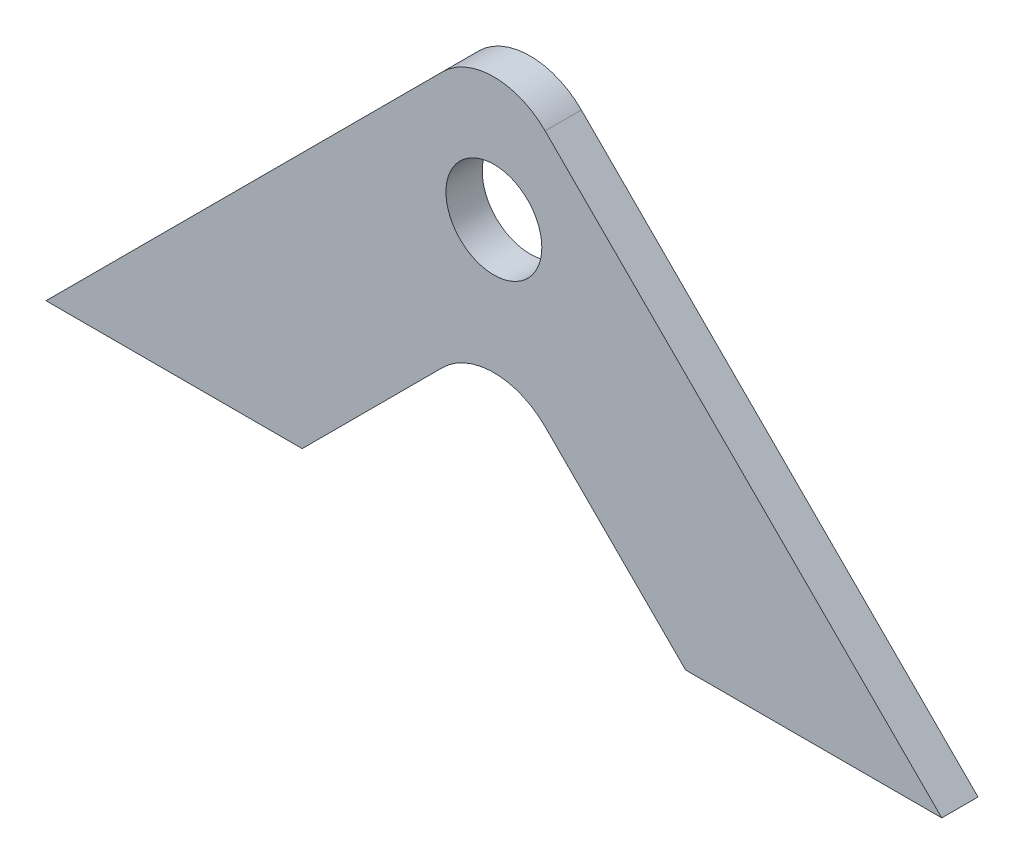
SolidWorks part; units mm, degrees
material "AISI 4130 Steel, annealed at 865C"
ref_plane "Front Plane" through (0, 0, 0) normal (0, 0, 1) x (1, 0, 0)
ref_plane "Top Plane" through (0, 0, 0) normal (0, 1, 0) x (1, 0, 0)
ref_plane "Right Plane" through (0, 0, 0) normal (1, 0, 0) x (0, 0, -1)
sketch "Sketch1" plane through (0, 0, 0) normal (0, 0, 1) x (1, 0, 0)
  line L3 (0, 0) -> (38.1, 38.0993) construction
  line L4 (0, 0) -> (76.2, 0) construction
  line L5 (38.1, 38.0993) -> (76.2, 0) construction
  line L6 (-13.4705, 0) -> (33.6099, 47.0795)
  line L7 (42.5901, 47.0795) -> (89.6705, 0)
  line L8 (89.6705, 0) -> (-13.4705, 0)
  line L9 (8.9803, 0) -> (33.6099, 24.6291)
  line L10 (42.5901, 24.6291) -> (67.2197, 0)
  line L11 (-1.1513, 12.319) -> (77.3513, 12.319)
  circle A0 centre (38.1, 38.0993) radius 4.1999
  arc A1 (33.6099, 24.6291) -> (42.5901, 24.6291) centre (38.1, 20.1389) cw
  arc A2 (42.5901, 47.0795) -> (33.6099, 47.0795) centre (38.1, 42.5894) ccw
  point P6 (38.1, 0)
  dimension "D3" = 8.3998
  dimension "D4" = 9.525
  dimension "D7" = 6.35
  dimension "D1" = 53.881
  dimension "D2" = 76.2
  dimension "D5" = 6.35
  dimension "D6" = 6.35
  dimension "D8" = 12.319
extrude "Boss-Extrude2" add sketch "Sketch1" along normal blind 3.175 contours L7 A2 L6 L11 A1 A0
